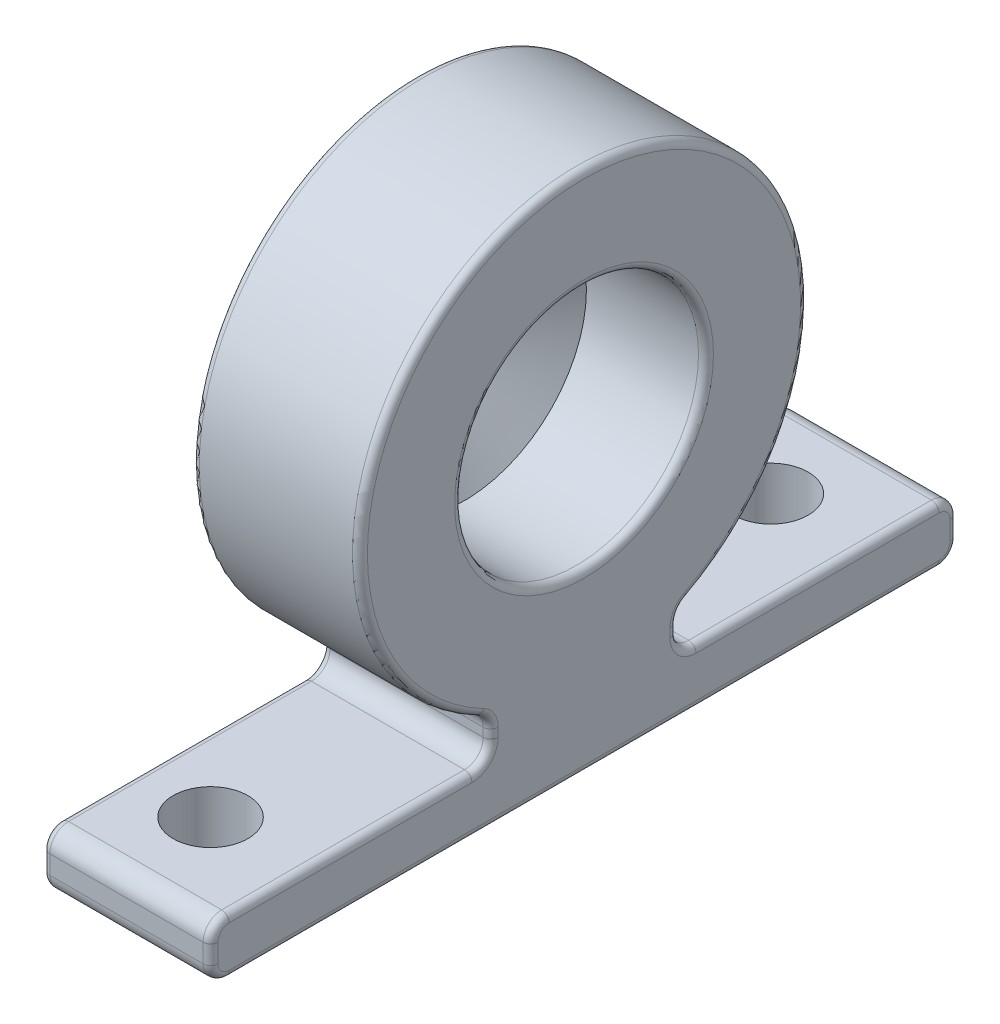
SolidWorks part; units mm, degrees
ref_plane "前视基准面" through (0, 0, 0) normal (0, 0, 1) x (1, 0, 0)
ref_plane "上视基准面" through (0, 0, 0) normal (0, 1, 0) x (1, 0, 0)
ref_plane "右视基准面" through (0, 0, 0) normal (1, 0, 0) x (0, 0, -1)
sketch "草图1" plane through (0, 0, 0) normal (1, 0, 0) x (0, 0, -1)
  line L0 (-9.5, -6.5) -> (-3, -6.5)
  line L1 (-10, -7) -> (-10, -7.5)
  line L2 (10, -7) -> (10, -7.5)
  line L5 (-9.5, -8) -> (9.5, -8)
  line L6 (3, -6.5) -> (9.5, -6.5)
  line L7 (-2.5, -5.7663) -> (-2.5, -6)
  line L8 (2.5, -5.7663) -> (2.5, -6)
  arc A0 (2.7692, -5.3227) -> (-2.7692, -5.3227) centre (0, 0) ccw
  arc A1 (10, -7.5) -> (9.5, -8) centre (9.5, -7.5) cw
  arc A2 (10, -7) -> (9.5, -6.5) centre (9.5, -7) ccw
  arc A3 (-9.5, -6.5) -> (-10, -7) centre (-9.5, -7) ccw
  arc A4 (-9.5, -8) -> (-10, -7.5) centre (-9.5, -7.5) cw
  arc A5 (2.5, -5.7663) -> (2.7692, -5.3227) centre (3, -5.7663) cw
  arc A6 (2.5, -6) -> (3, -6.5) centre (3, -6) ccw
  arc A7 (-2.5, -6) -> (-3, -6.5) centre (-3, -6) cw
  arc A8 (-2.5, -5.7663) -> (-2.7692, -5.3227) centre (-3, -5.7663) ccw
  point P14 (3.9686, -6.5)
  dimension "D1" = 6.5
  dimension "D2" = 0.5
  dimension "D3" = 0.5
  dimension "D9" = 8
extrude "凸台-拉伸1" add sketch "草图1" along normal blind 4.5
sketch "草图2" plane through (0, 0, 0) normal (-1, 0, 0) x (0, 0, 1)
  circle A0 centre (0, 0) radius 2
extrude "切除-拉伸1" cut sketch "草图2" against normal blind 10
hole_wizard "5/16-18 螺纹孔1" positions "草图3" profile "草图4" tap size "5/16-18" standard "ANSI Inch"
sketch "草图3" plane through (4.5, 0, 0) normal (1, 0, 0) x (0, 0, -1)
  point P0 (0, 0)
sketch "草图4" plane through (4.5, 0, 0) normal (0, 1, 0) x (0, 0, -1)
  line L0 (0, 0) -> (0, 5.1611)
  line L1 (0, 5.1611) -> (3.2639, 3.2)
  line L2 (3.2639, 3.2) -> (3.2639, 0)
  line L5 (3.2639, 0) -> (0, 0)
  line L10 (0, 5.1611) -> (-3.2639, 3.2) construction
  line L11 (0, -6.35) -> (0, 107.95) construction
  dimension "螺纹孔钻头直径" = 6.5278
  dimension "螺纹孔钻头深度" = 3.2
  dimension "导头角度" = 118
cosmetic thread "孔螺蚊线1" parameters "D1"=3.2, "D2"=7.9375
sketch "草图5" plane through (0, -6.5, 0) normal (0, 1, 0) x (1, 0, 0)
  circle A0 centre (2, -7.5) radius 1
  circle A1 centre (2, 7.5) radius 1
extrude "切除-拉伸2" cut sketch "草图5" against normal up to next
fillet "圆角1" radius 0.2 34 edges at (0, -5.8831, 2.5) (0, -6.3536, 2.6464) (0, -6.5, 6.25) (0, -6.6464, 9.8536) (0, -7.25, 10) (0, -7.8536, 9.8536) (0, -8, 0) (0, -7.8536, -9.8536) (0, -7.25, -10) (0, -6.6464, -9.8536) (0, -6.5, -6.25) (0, -6.3536, -2.6464) (0, -5.8831, -2.5) (0, -5.5068, -2.5726) (0, 6, 0) (0, -5.5068, 2.5726) (0, 0, 2) (4.5, 6, 0) (4.5, -5.5068, -2.5726) (4.5, -5.8831, -2.5) (4.5, -6.3536, -2.6464) (4.5, -6.5, -6.25) (4.5, -6.6464, -9.8536) (4.5, -7.25, -10) (4.5, -7.8536, -9.8536) (4.5, -8, 0) (4.5, -7.8536, 9.8536) (4.5, -7.25, 10) (4.5, -6.6464, 9.8536) (4.5, -6.5, 6.25) (4.5, -6.3536, 2.6464) (4.5, -5.8831, 2.5) (4.5, -5.5068, 2.5726) (4.5, 0, -3.2639)
